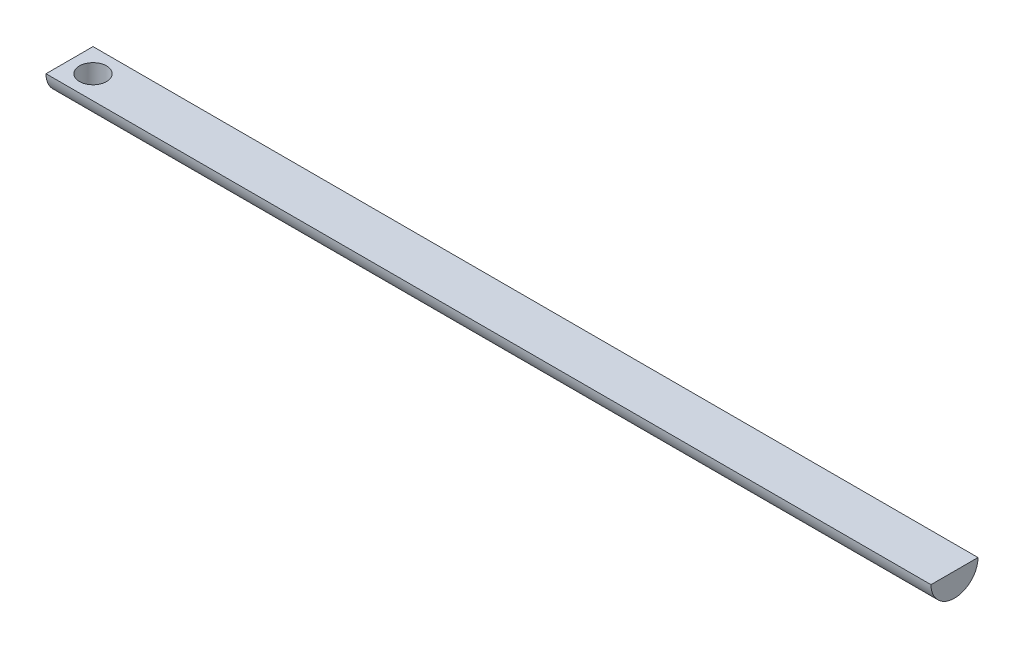
SolidWorks part; units mm, degrees
material "6061-T6 (SS)"
ref_plane "Front Plane" through (0, 0, 0) normal (0, 0, 1) x (1, 0, 0)
ref_plane "Top Plane" through (0, 0, 0) normal (0, 1, 0) x (1, 0, 0)
ref_plane "Right Plane" through (0, 0, 0) normal (1, 0, 0) x (0, 0, -1)
sketch "Sketch1" plane through (0, 0, 0) normal (1, 0, 0) x (0, 0, -1)
  line L0 (-4.7625, 0) -> (4.7625, 0)
  arc A0 (-4.7625, 0) -> (4.7625, 0) centre (0, 0) ccw
  point P3 (0, 0)
  dimension "D1" = 9.525
extrude "Boss-Extrude1" add sketch "Sketch1" along normal blind 160 and the other way blind 19.2384
hole_wizard "M5 Clearance Hole1" positions "Sketch2" profile "Sketch3" hole size "M5" standard "ANSI Metric"
sketch "Sketch2" plane through (0, 0, 0) normal (0, 1, 0) x (1, 0, 0)
  line L0 (-19.2384, 4.7625) -> (-19.2384, -4.7625) construction
  point P0 (-14.4759, 0)
  dimension "D1" = 4.7625
sketch "Sketch3" plane through (-14.4759, 0, 0) normal (1, 0, 0) x (0, 0, 1)
  line L0 (0, 0) -> (0, 14.3524)
  line L1 (0, 14.3524) -> (2.75, 12.7)
  line L2 (2.75, 12.7) -> (2.75, 0)
  line L5 (2.75, 0) -> (0, 0)
  line L10 (0, 14.3524) -> (-2.75, 12.7) construction
  line L11 (0, -6.35) -> (0, 107.95) construction
  dimension "Hole Dia." = 5.5
  dimension "Hole Depth" = 12.7
  dimension "Drill Angle" = 118
